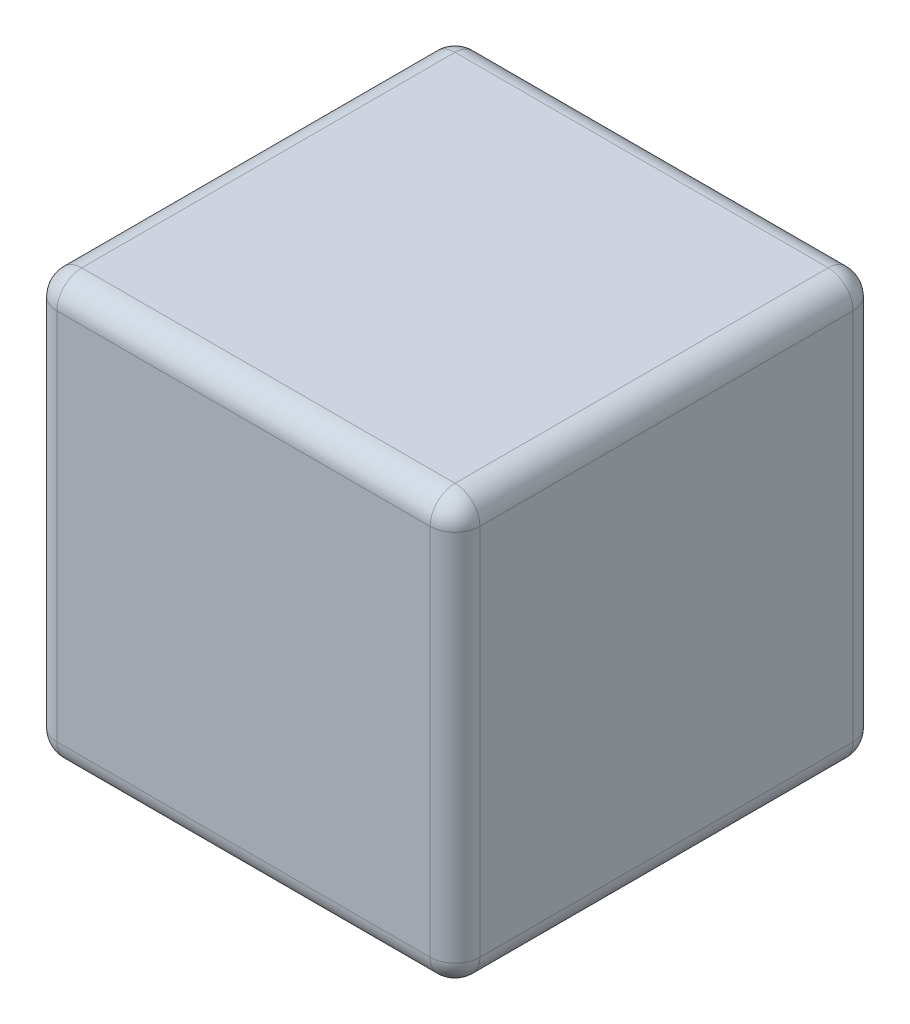
SolidWorks part; units mm, degrees
ref_plane "前视基准面" through (0, 0, 0) normal (0, 0, 1) x (1, 0, 0)
ref_plane "上视基准面" through (0, 0, 0) normal (0, 1, 0) x (1, 0, 0)
ref_plane "右视基准面" through (0, 0, 0) normal (1, 0, 0) x (0, 0, -1)
sketch "草图1" plane through (0, 0, 0) normal (0, 1, 0) x (1, 0, 0)
  line L1 (0, 0) -> (17, 0)
  line L2 (0, 0) -> (0, 17)
  line L3 (0, 17) -> (17, 17)
  line L4 (17, 0) -> (17, 17)
  dimension "D1" = 17
  dimension "D2" = 17
extrude "凸台-拉伸1" add sketch "草图1" along normal blind 17
fillet "圆角1" radius 1 12 edges at (8.5, 0, -17) (17, 8.5, -17) (17, 0, -8.5) (8.5, 17, -17) (17, 17, -8.5) (0, 8.5, -17) (0, 17, -8.5) (0, 0, -8.5) (0, 8.5, 0) (8.5, 17, 0) (17, 8.5, 0) (8.5, 0, 0)
